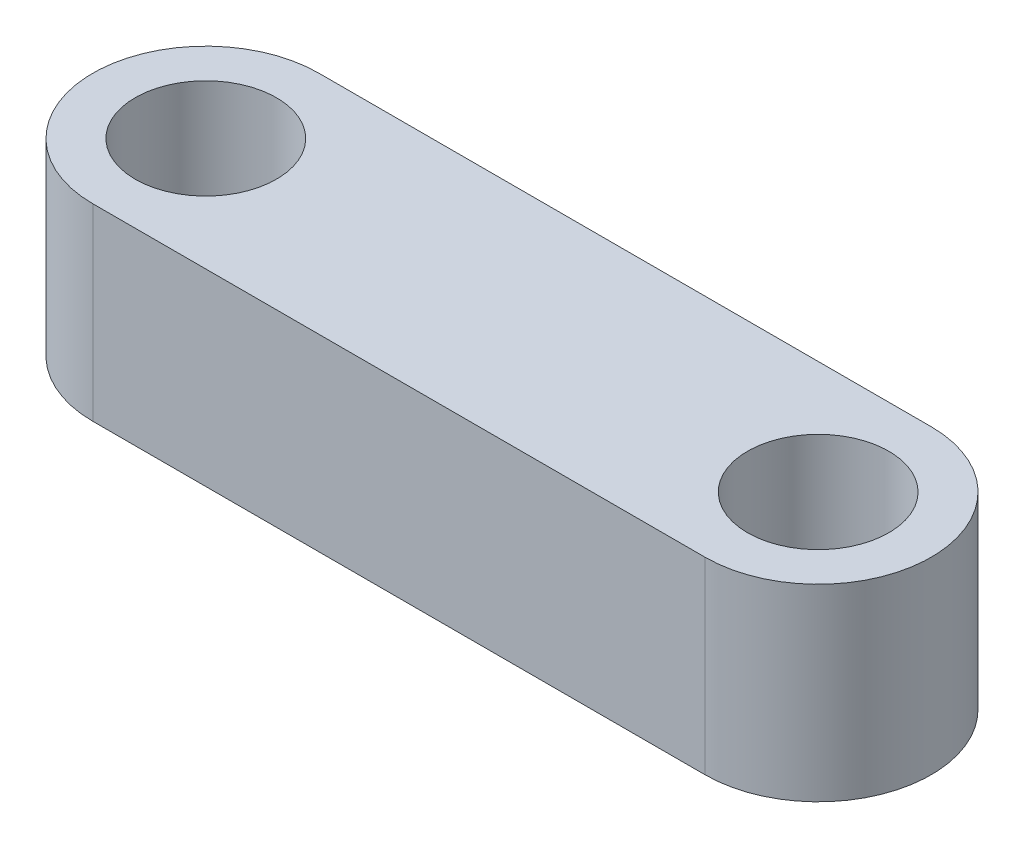
SolidWorks part; units mm, degrees
ref_plane "Front Plane" through (0, 0, 0) normal (0, 0, 1) x (1, 0, 0)
ref_plane "Top Plane" through (0, 0, 0) normal (0, 1, 0) x (1, 0, 0)
ref_plane "Right Plane" through (0, 0, 0) normal (1, 0, 0) x (0, 0, -1)
sketch "Sketch1" plane through (0, 0, 0) normal (0, 1, 0) x (1, 0, 0)
  line L0 (-29.8353, 4.0295) -> (-19.5165, 4.0295) construction
  line L1 (-29.8353, 4.0295) -> (-19.5165, 4.0295) construction
  line L2 (-29.8353, 5.9345) -> (-19.5165, 5.9345)
  line L3 (-29.8353, 2.1245) -> (-19.5165, 2.1245)
  circle A0 centre (-29.8353, 4.0295) radius 1.1906
  circle A1 centre (-19.5165, 4.0295) radius 1.1906
  arc A2 (-29.8353, 5.9345) -> (-29.8353, 2.1245) centre (-29.8353, 4.0295) ccw
  arc A3 (-19.5165, 2.1245) -> (-19.5165, 5.9345) centre (-19.5165, 4.0295) ccw
  point P5 (-24.6759, 4.0295)
extrude "Boss-Extrude1" add sketch "Sketch1" along normal blind 3.175
